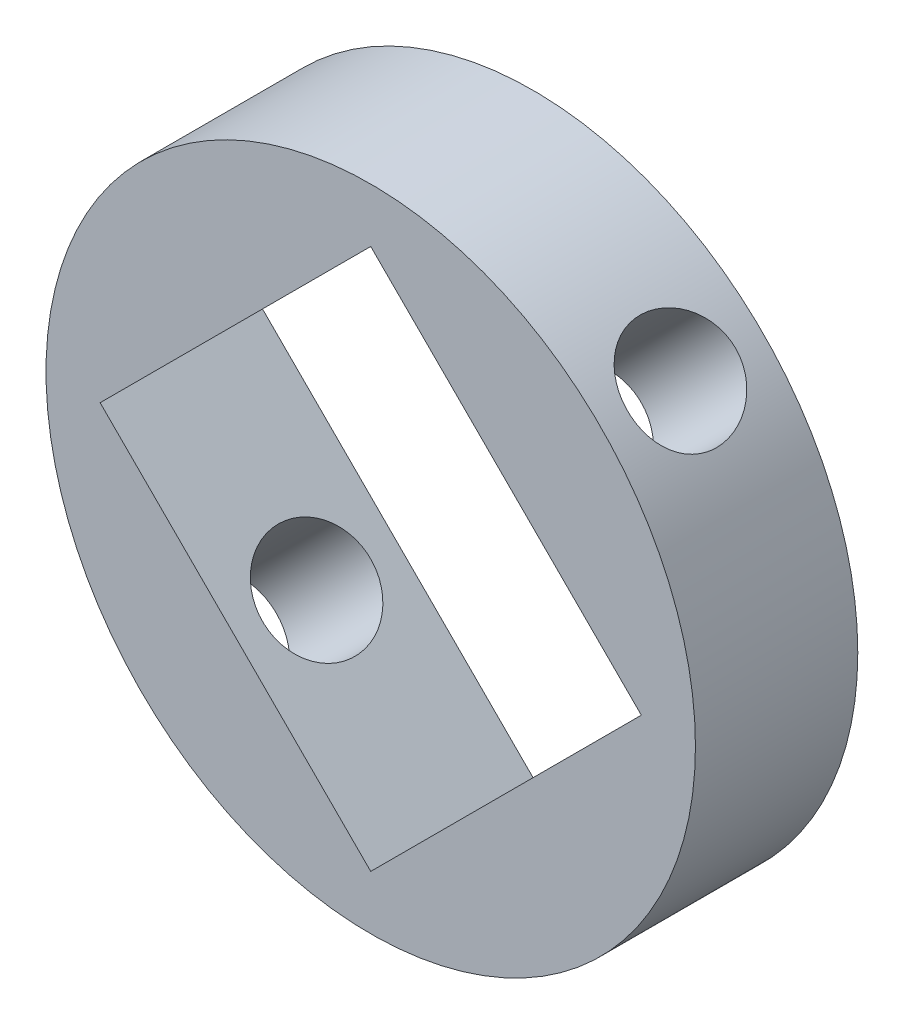
SolidWorks part; units mm, degrees
ref_plane "前视基准面" through (0, 0, 0) normal (0, 0, 1) x (1, 0, 0)
ref_plane "上视基准面" through (0, 0, 0) normal (0, 1, 0) x (1, 0, 0)
ref_plane "右视基准面" through (0, 0, 0) normal (1, 0, 0) x (0, 0, -1)
sketch "草图1" plane through (0, 0, 0) normal (0, 0, 1) x (1, 0, 0)
  circle A0 centre (0, 0) radius 12
extrude "凸台-拉伸1" add sketch "草图1" against normal blind 6
sketch "草图2" plane through (0, 0, 0) normal (0, 0, 1) x (1, 0, 0)
  line L1 (10, 0) -> (0, 10)
  line L2 (0, 10) -> (-10, 0)
  line L3 (-10, 0) -> (0, -10)
  line L4 (0, -10) -> (10, 0)
extrude "切除-拉伸1" cut sketch "草图2" against normal blind 10 contours L1 L2 L3 L4
sketch "草图7" plane through (5, 5, 0) normal (-0.7071, -0.7071, 0) x (0, 0, 1)
  line L0 (-6, -7.0711) -> (-6, 7.0711) construction
  line L1 (0, -7.0711) -> (0, 7.0711) construction
  line L2 (-6, 0) -> (0, 0)
  circle A0 centre (-3, 0) radius 2
  point P0 (-6, 0)
  point P1 (0, 0)
  point P8 (-3, 0)
extrude "切除-拉伸6" cut sketch "草图7" against normal blind 11 contours L2 A0 | L2 A0
sketch "草图8" plane through (-5, -5, 0) normal (0.7071, 0.7071, 0) x (0, 0, -1)
  line L0 (6, 0) -> (0, 0)
  line L1 (6, 7.0711) -> (6, -7.0711) construction
  line L2 (0, 7.0711) -> (0, -7.0711) construction
  circle A0 centre (3, 0) radius 2
  point P6 (3, 0)
extrude "切除-拉伸7" cut sketch "草图8" against normal blind 11 contours L0 A0 | L0 A0
